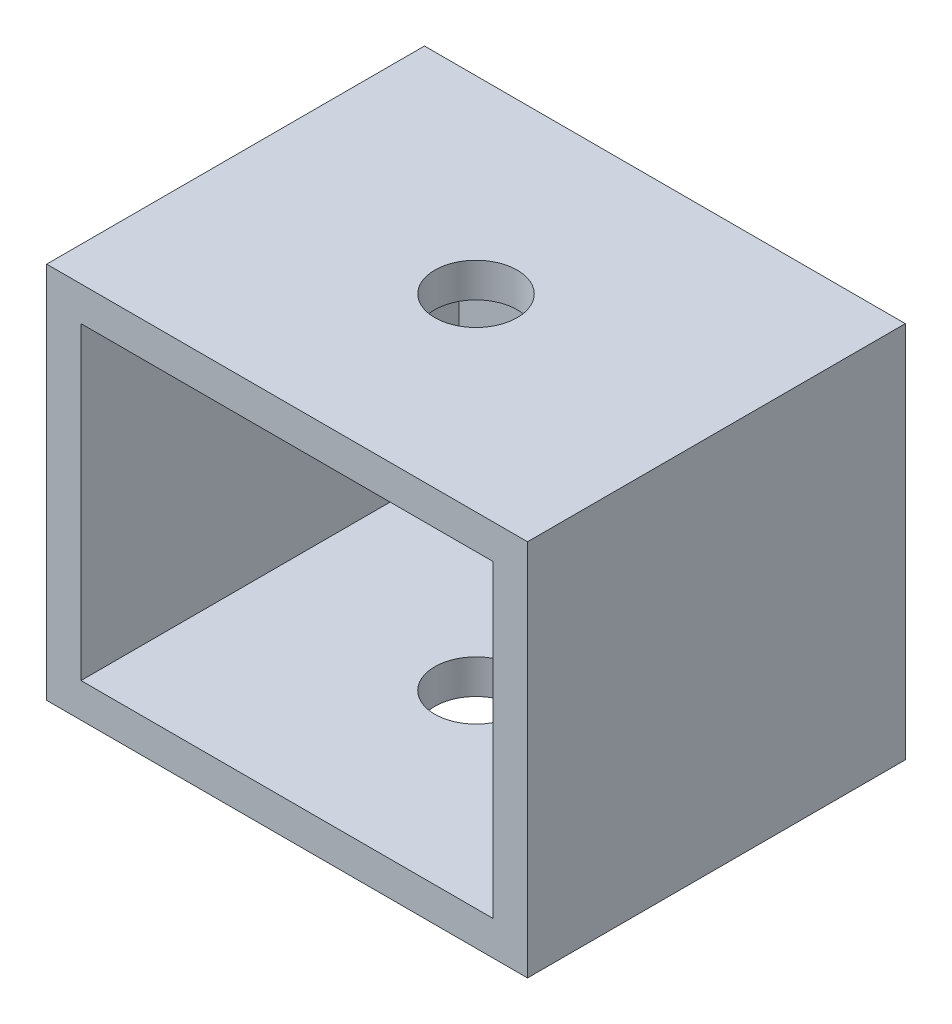
SolidWorks part; units mm, degrees
material "CA"
ref_plane "Front Plane" through (0, 0, 0) normal (0, 0, 1) x (1, 0, 0)
ref_plane "Top Plane" through (0, 0, 0) normal (0, 1, 0) x (1, 0, 0)
ref_plane "Right Plane" through (0, 0, 0) normal (1, 0, 0) x (0, 0, -1)
sketch "Sketch1" plane through (0, 0, 0) normal (0, 0, 1) x (1, 0, 0)
  line L1 (0, 0) -> (-70, 0)
  line L2 (0, 0) -> (0, 55)
  line L3 (0, 55) -> (-70, 55)
  line L4 (-70, 0) -> (-70, 55)
  dimension "D1" = 70
  dimension "D2" = 55
extrude "Boss-Extrude1" add sketch "Sketch1" along normal blind 5
sketch "Sketch2" plane through (0, 0, 5) normal (0, 0, 1) x (1, 0, 0)
  line L0 (0, 55) -> (-70, 55) construction
  line L1 (-65, 50) -> (-60, 50)
  line L2 (-65, 50) -> (-65, 5)
  line L3 (-65, 5) -> (-60, 5)
  line L4 (-60, 50) -> (-60, 5)
  line L9 (-10.0196, 50) -> (-5, 50)
  line L10 (-10.0196, 50) -> (-10.0196, 5)
  line L11 (-10.0196, 5) -> (-5, 5)
  line L12 (-5, 50) -> (-5, 5)
  line L13 (-70, 55) -> (-70, 0) construction
  line L14 (0, 0) -> (0, 55) construction
  line L15 (-70, 0) -> (0, 0) construction
  dimension "D1" = 5
  dimension "D2" = 5
  dimension "D3" = 5
  dimension "D4" = 5
  dimension "D5" = 5
  dimension "D6" = 5.0196
  dimension "D8" = 5
  dimension "D9" = 5
extrude "Cut-Extrude1" cut sketch "Sketch2" against normal blind 5
sketch "Sketch6" plane through (0, 0, 5) normal (0, 0, 1) x (1, 0, 0)
  line L0 (0, 55) -> (-70, 55) construction
  line L1 (-70, 0) -> (-65, 0)
  line L2 (-70, 0) -> (-70, 55)
  line L3 (-70, 55) -> (-65, 55)
  line L4 (-65, 5) -> (-65, 50)
  line L6 (0, 0) -> (-5, 0)
  line L7 (0, 0) -> (0, 55)
  line L8 (0, 55) -> (-5, 55)
  line L9 (-5, 5) -> (-5, 50)
  line L10 (-5, 50) -> (-65, 50)
  line L12 (-5, 55) -> (-65, 55)
  line L13 (-65, 5) -> (-5, 5)
  line L15 (-65, 0) -> (-5, 0)
  dimension "D1" = 5
extrude "Boss-Extrude4" add sketch "Sketch6" along normal blind 50
sketch "Sketch7" plane through (0, 55, 0) normal (0, 1, 0) x (1, 0, 0)
  line L0 (0, -55) -> (0, 0) construction
  line L1 (0, 0) -> (-70, 0) construction
  circle A0 centre (-35, -27.5) radius 6
  dimension "D1" = 35
  dimension "D2" = 27.5
extrude "Cut-Extrude2" cut sketch "Sketch7" against normal blind 70
sketch "Sketch8" plane through (-10.0196, 0, 0) normal (1, 0, 0) x (0, 0, -1)
  line L0 (-5, 50) -> (-5, 5) construction
  line L1 (0, 50) -> (-5, 50)
  line L2 (0, 50) -> (0, 40)
  line L3 (0, 40) -> (-5, 40)
  line L4 (-5, 50) -> (-5, 40)
  dimension "D1" = 10
extrude "Boss-Extrude5" add sketch "Sketch8" along normal blind 5
sketch "Sketch9" plane through (-60, 0, 0) normal (-1, 0, 0) x (0, 0, 1)
  line L0 (5, 5) -> (5, 50) construction
  line L1 (0, 50) -> (5, 50)
  line L2 (0, 50) -> (0, 40)
  line L3 (0, 40) -> (5, 40)
  line L4 (5, 50) -> (5, 40)
  dimension "D1" = 10
extrude "Boss-Extrude6" add sketch "Sketch9" along normal blind 5
